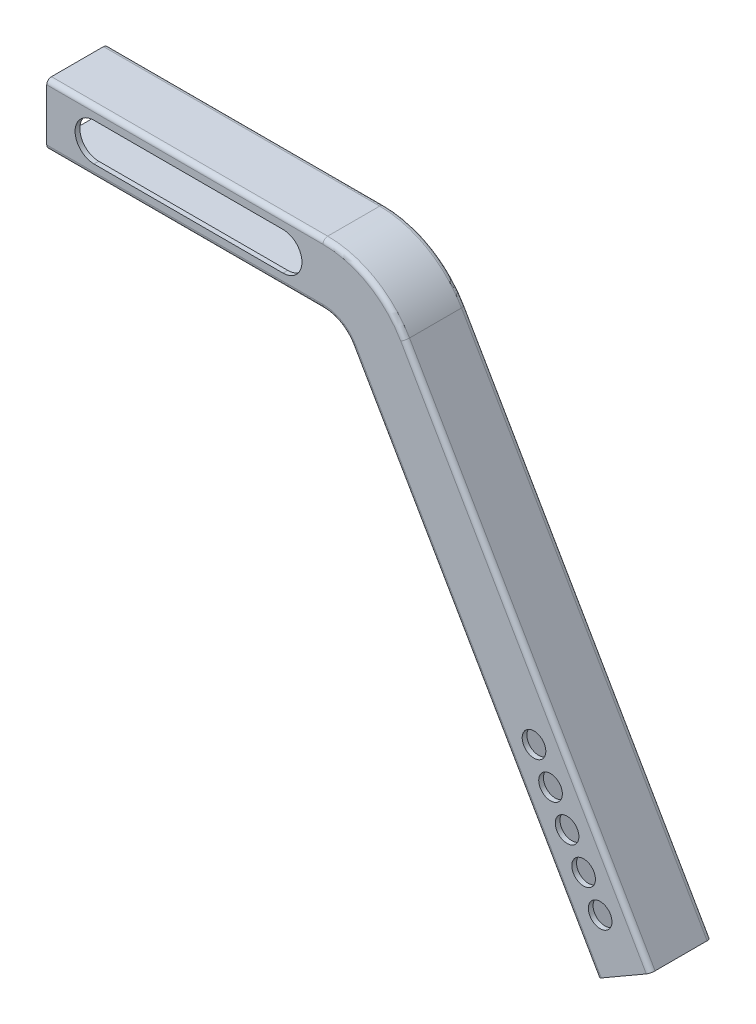
SolidWorks part; units mm, degrees
material "Plain Carbon Steel"
ref_plane "Front Plane" through (0, 0, 0) normal (0, 0, 1) x (1, 0, 0)
ref_plane "Top Plane" through (0, 0, 0) normal (0, 1, 0) x (1, 0, 0)
ref_plane "Right Plane" through (0, 0, 0) normal (1, 0, 0) x (0, 0, -1)
sketch "Sketch1" plane through (0, 0, 0) normal (0, 0, 1) x (1, 0, 0)
  line L0 (-172.047, 25.4) -> (-23.5764, 25.4)
  line L1 (20.4177, 0) -> (152.4, -228.6)
  line L2 (-172.047, -7.62) -> (-23.5764, -7.62)
  line L3 (-8.1784, -16.51) -> (123.8038, -245.11)
  line L4 (-172.047, 25.4) -> (-172.047, -7.62)
  line L5 (123.8038, -245.11) -> (152.4, -228.6)
  arc A0 (-23.5764, 25.4) -> (20.4177, 0) centre (-23.5764, -25.4) cw
  arc A1 (-23.5764, -7.62) -> (-8.1784, -16.51) centre (-23.5764, -25.4) cw
  point P6 (5.753, 25.4)
  dimension "D6" = 50.8
  dimension "D1" = 120
  dimension "D2" = 177.8
  dimension "D3" = 254
  dimension "D4" = 25.4
  dimension "D5" = 152.4
  dimension "D7" = 33.02
extrude "Boss-Extrude1" add sketch "Sketch1" along normal blind 33.02
shell "Shell1" thickness 2.54
sketch "Sketch2" plane through (137.0867, -237.4411, 0) normal (0.5, -0.866, 0) x (0.866, 0.5, 0)
  line L0 (17.6823, 33.02) -> (17.6823, 0) construction
  line L1 (-12.7977, 2.54) -> (15.1423, 2.54)
  line L2 (-12.7977, 2.54) -> (-12.7977, 30.48)
  line L3 (-12.7977, 30.48) -> (15.1423, 30.48)
  line L4 (15.1423, 2.54) -> (15.1423, 30.48)
  line L5 (-12.7977, 2.54) -> (15.1423, 30.48) construction
  line L6 (-12.7977, 30.48) -> (15.1423, 2.54) construction
  line L7 (-15.3377, 33.02) -> (-15.3377, 0) construction
  line L8 (-15.3377, 33.02) -> (17.6823, 33.02) construction
  line L9 (-15.3377, 0) -> (17.6823, 0) construction
  point P0 (1.1723, 16.51)
  dimension "D1" = 2.54
  dimension "D2" = 2.54
  dimension "D3" = 2.54
  dimension "D4" = 2.54
extrude "Cut-Extrude1" cut sketch "Sketch2" against normal up to next
sketch "Sketch3" plane through (0, 0, 33.02) normal (0, 0, 1) x (1, 0, 0)
  line L0 (-172.047, 25.4) -> (-172.047, -7.62) construction
  line L1 (-146.647, 19.05) -> (-45.047, 19.05)
  line L2 (-146.647, -1.27) -> (-50.127, -1.27)
  line L7 (-50.127, -1.27) -> (-45.047, -1.27)
  line L8 (-172.047, -7.62) -> (-23.5764, -7.62) construction
  arc A0 (-146.647, 19.05) -> (-146.647, -1.27) centre (-146.647, 8.89) ccw
  arc A1 (-45.047, -1.27) -> (-45.047, 19.05) centre (-45.047, 8.89) ccw
  dimension "D1" = 10.16
  dimension "D2" = 25.4
  dimension "D4" = 127
  dimension "D5" = 16.51
  dimension "D3" = 121.92
extrude "Cut-Extrude2" cut sketch "Sketch3" against normal blind 2.54
sketch "Sketch4" plane through (0, 0, 0) normal (0, 0, -1) x (-1, 0, 0)
  line L0 (172.047, 25.4) -> (172.047, -7.62) construction
  line L1 (23.5764, 25.4) -> (172.047, 25.4) construction
  line L12 (141.567, -1.27) -> (146.647, -1.27)
  line L13 (146.647, 19.05) -> (45.047, 19.05)
  line L14 (45.047, -1.27) -> (141.567, -1.27)
  arc A12 (146.647, -1.27) -> (146.647, 19.05) centre (146.647, 8.89) ccw
  arc A13 (45.047, 19.05) -> (45.047, -1.27) centre (45.047, 8.89) ccw
  dimension "D1" = 10.16
  dimension "D2" = 25.4
  dimension "D3" = 30.48
  dimension "D4" = 127
  dimension "D5" = 16.51
extrude "Cut-Extrude3" cut sketch "Sketch4" against normal blind 2.54
sketch "Sketch5" plane through (0, 0, 33.02) normal (0, 0, 1) x (1, 0, 0)
  line L0 (138.1019, -236.855) -> (28.1279, -46.3744) construction
  line L1 (123.8038, -245.11) -> (152.4, -228.6) construction
  line L4 (-172.047, 25.4) -> (-172.047, -7.62) construction
  circle A0 centre (125.4019, -214.858) radius 6.35
  circle A1 centre (116.5119, -199.46) radius 6.35
  circle A2 centre (107.6219, -184.0621) radius 6.35
  circle A3 centre (98.7319, -168.6642) radius 6.35
  circle A4 centre (89.8419, -153.2662) radius 6.35
  dimension "D1" = 12.7
  dimension "D3" = 25.4
  dimension "D4" = 261.8889
  dimension "D2" = 5
extrude "Cut-Extrude4" cut sketch "Sketch5" against normal up to next
fillet "Fillet1" radius 2.54 12 edges at (57.8127, -130.81, 0) (-14.6864, -10.0021, 0) (57.8127, -130.81, 33.02) (-14.6864, -10.0021, 33.02) (86.4089, -114.3, 0) (1.8236, 18.5941, 0) (86.4089, -114.3, 33.02) (1.8236, 18.5941, 33.02) (-97.8117, -7.62, 0) (-97.8117, -7.62, 33.02) (-97.8117, 25.4, 0) (-97.8117, 25.4, 33.02)
